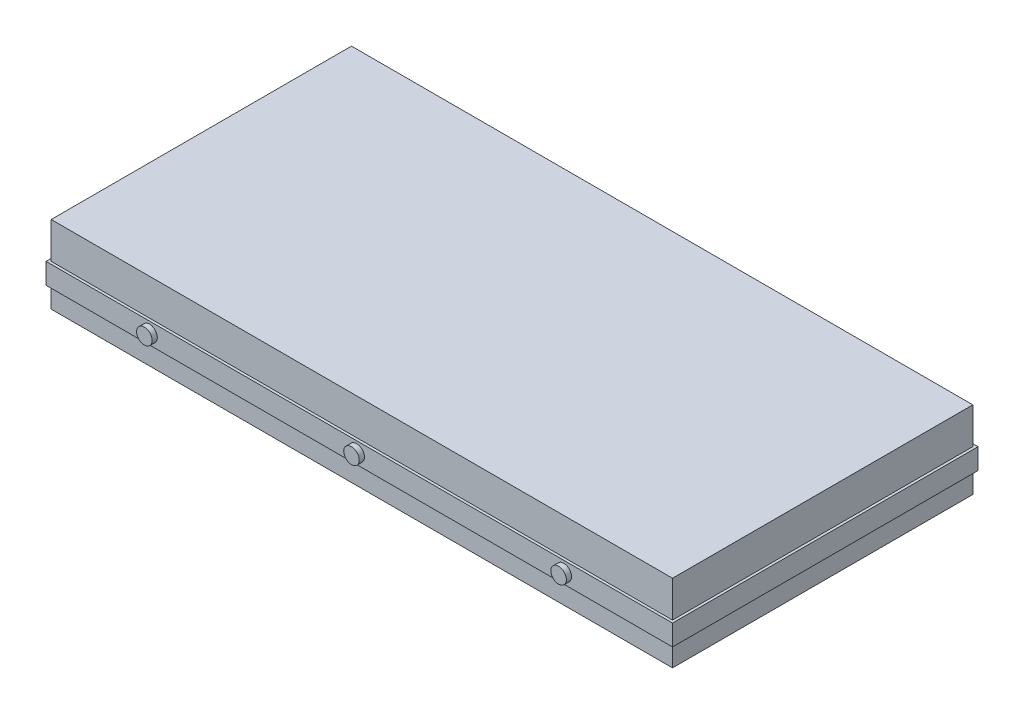
SolidWorks part; units mm, degrees
ref_plane "Płaszczyzna przednia" through (0, 0, 0) normal (0, 0, 1) x (1, 0, 0)
ref_plane "Płaszczyzna górna" through (0, 0, 0) normal (0, 1, 0) x (1, 0, 0)
ref_plane "Płaszczyzna prawa" through (0, 0, 0) normal (1, 0, 0) x (0, 0, -1)
sketch "Szkic1" plane through (0, 0, 0) normal (0, 1, 0) x (1, 0, 0)
  line L0 (0, 0) -> (0, 580)
  line L1 (0, 580) -> (1200, 580)
  line L2 (1200, 0) -> (0, 0)
  line L3 (1200, 0) -> (1200, 580)
  dimension "D1" = 580
  dimension "D2" = 1200
extrude "Dodanie-wyciągnięcie1" add sketch "Szkic1" along normal blind 150
ref_plane "Płaszczyzna1" through (0, 60, 0) normal (0, 1, 0) x (1, 0, 0)
sketch "Szkic2" plane through (0, 60, 0) normal (0, 1, 0) x (1, 0, 0)
  line L0 (0, 0) -> (1200, 0)
  line L2 (1200, 580) -> (0, 580)
  line L3 (0, 580) -> (0, 0)
  line L5 (1200, 580) -> (1200, 0)
  line L6 (1205, 585) -> (-5, 585)
  line L7 (-5, 585) -> (-5, -5)
  line L8 (-5, -5) -> (1205, -5)
  line L9 (1205, 585) -> (1205, -5)
  dimension "D1" = 580
  dimension "D2" = 1200
  dimension "D3" = 5
extrude "Dodanie-wyciągnięcie2" add sketch "Szkic2" along normal mid plane 40
sketch "Szkic3" plane through (0, 0, 5) normal (0, 0, 1) x (1, 0, 0)
  line L0 (-5, 80) -> (-5, 60) construction
  line L1 (-5, 80) -> (-5, 40) construction
  line L2 (-5, 60) -> (1195, 60) construction
  line L3 (-5, 60) -> (195, 60) construction
  circle A0 centre (195, 60) radius 15
extrude "Dodanie-wyciągnięcie3" add sketch "Szkic3" along normal blind 10
pattern_linear "Szyk liniowy1" count 3 spacing 400 along (1, 0, 0) of "Dodanie-wyciągnięcie3"
ref_plane "Płaszczyzna2" through (0, 0, -290) normal (0, 0, 1) x (1, 0, 0)
mirror "Lustro1" about plane through (0, 0, -290) normal (0, 0, 1) of "Szyk liniowy1", "Dodanie-wyciągnięcie3"
